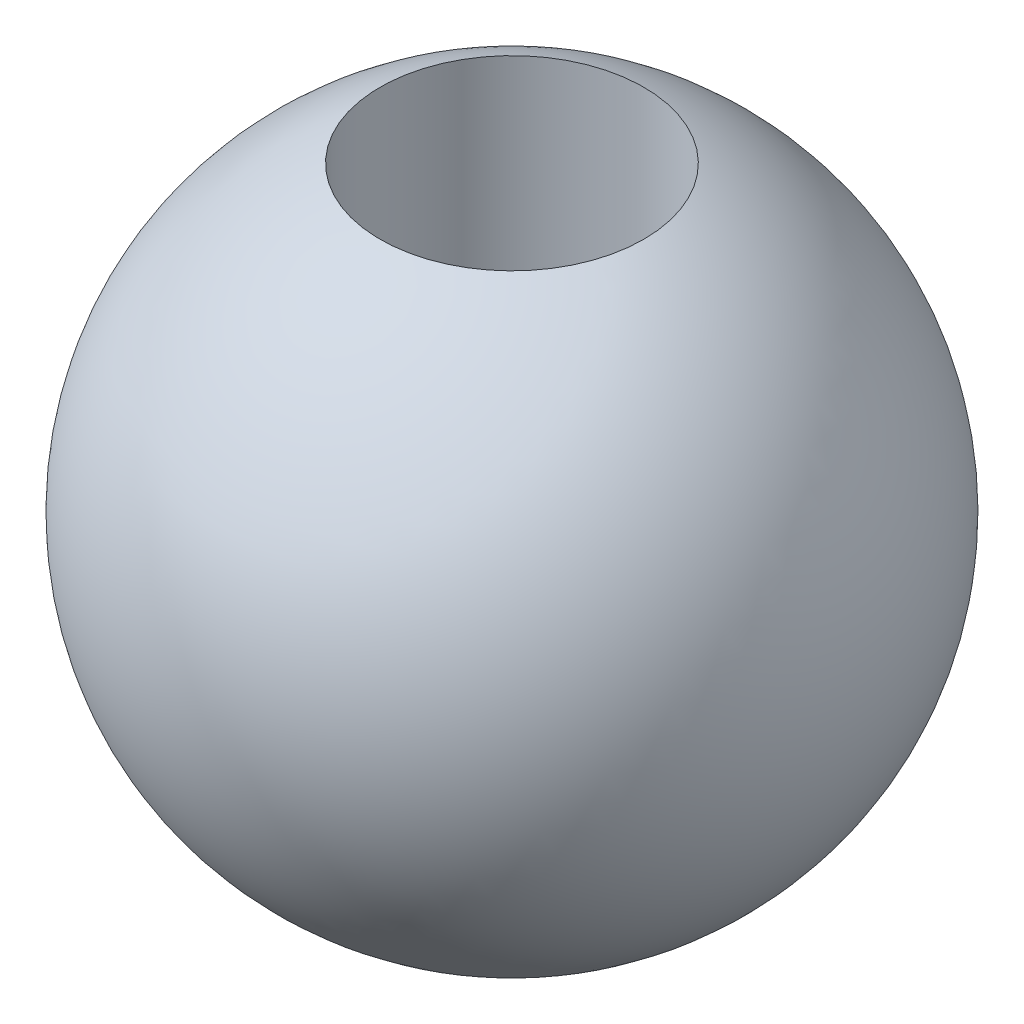
SolidWorks part; units mm, degrees
ref_plane "Plan de face" through (0, 0, 0) normal (0, 0, 1) x (1, 0, 0)
ref_plane "Plan de dessus" through (0, 0, 0) normal (0, 1, 0) x (1, 0, 0)
ref_plane "Plan de droite" through (0, 0, 0) normal (1, 0, 0) x (0, 0, -1)
sketch "Esquisse1" plane through (0, 0, 0) normal (0, 0, 1) x (1, 0, 0)
  line L3 (0, -2.5) -> (0, 2.5)
  arc A0 (0, 2.5) -> (0, -2.5) centre (0, 0) ccw
  point P3 (0, 0)
  dimension "D1" = 5
revolve "Révolution1" add sketch "Esquisse1" angle 360 about L3
sketch "Esquisse2" plane through (0, 0, 0) normal (0, 1, 0) x (1, 0, 0)
  circle A0 centre (0, 0) radius 1
  dimension "D1" = 2
extrude "Enlèv. mat.-Extru.1" cut sketch "Esquisse2" against normal mid plane 10
